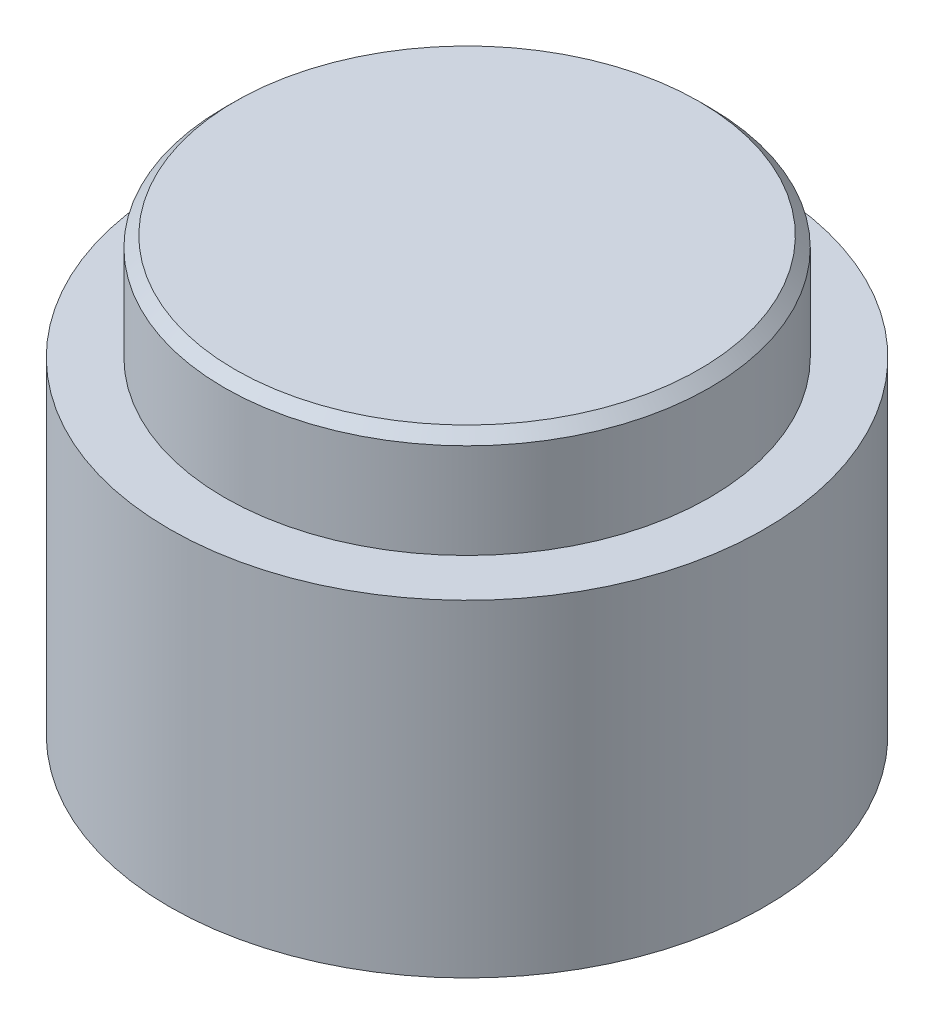
SolidWorks part; units mm, degrees
ref_plane "Front" through (0, 0, 0) normal (0, 0, 1) x (1, 0, 0)
ref_plane "Top" through (0, 0, 0) normal (0, 1, 0) x (1, 0, 0)
ref_plane "Right" through (0, 0, 0) normal (1, 0, 0) x (0, 0, -1)
sketch "Sketch1" plane through (0, 0, 0) normal (0, 1, 0) x (1, 0, 0)
  circle A0 centre (0, 0) radius 14.1
  dimension "D1" = 28.2
extrude "Extrude1" add sketch "Sketch1" along normal blind 15.5
sketch "Sketch2" plane through (0, 15.5, 0) normal (0, 1, 0) x (1, 0, 0)
  circle A0 centre (0, 0) radius 11.5
  dimension "D1" = 23
extrude "Extrude2" add sketch "Sketch2" along normal blind 5
chamfer "Chamfer1" distance 0.5 angle 45 1 edges at (0, 20.5, 11.5)
sketch "Sketch3" plane through (0, 0, 0) normal (0, -1, 0) x (1, 0, 0)
  circle A0 centre (0, 0) radius 11.618
extrude "Extrude3" cut sketch "Sketch3" against normal blind 3
